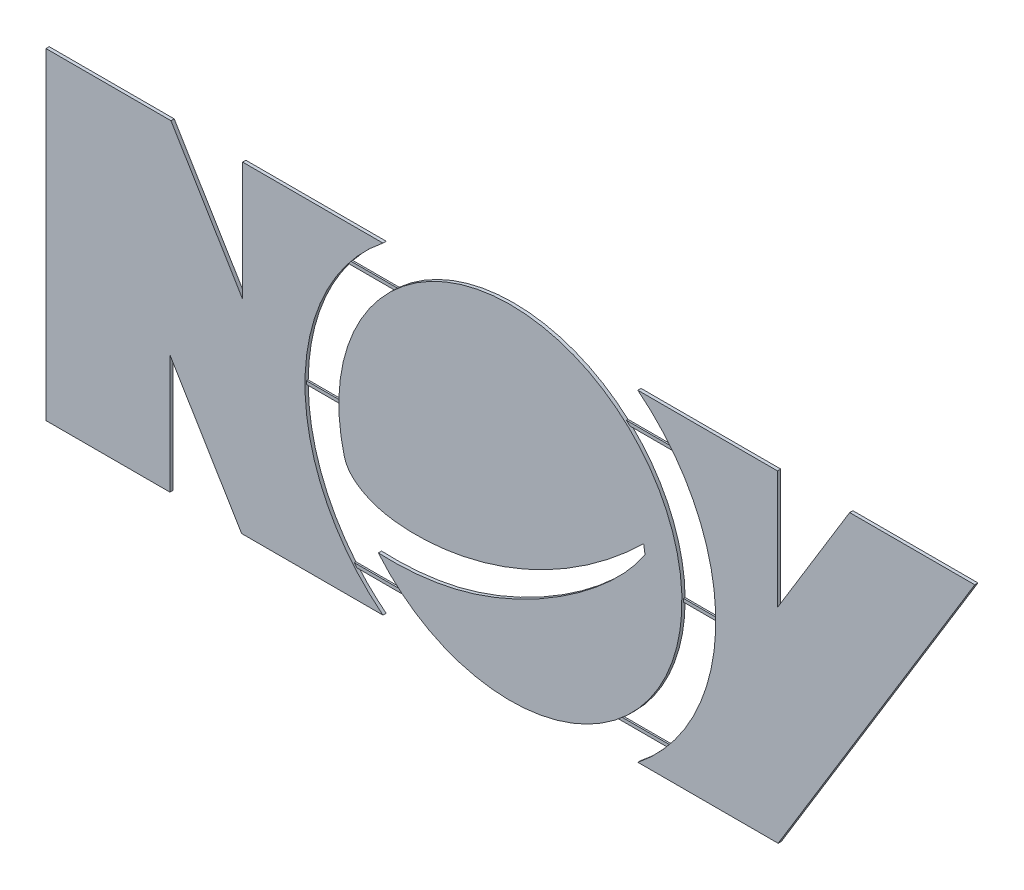
SolidWorks part; units mm, degrees
ref_plane "Front Plane" through (0, 0, 0) normal (0, 0, 1) x (1, 0, 0)
ref_plane "Top Plane" through (0, 0, 0) normal (0, 1, 0) x (1, 0, 0)
ref_plane "Right Plane" through (0, 0, 0) normal (1, 0, 0) x (0, 0, -1)
sketch "Sketch1" plane through (0, 0, 0) normal (0, 0, 1) x (1, 0, 0)
  line L0 (86.6339, 0.0014) -> (86.6339, 64.0014) construction
  line L1 (0, 62.0613) -> (23.3158, 62.0613)
  line L2 (23.3158, 62.0613) -> (36.6891, 39.8873)
  line L3 (36.6891, 39.8873) -> (36.6891, 62.0613)
  line L4 (36.6891, 62.0613) -> (62.8655, 62.0613)
  line L5 (0, 62.0613) -> (0, 1.95)
  line L6 (0, 1.95) -> (23.1112, 1.95)
  line L7 (23.1112, 1.95) -> (23.1112, 24.1454)
  line L8 (23.1112, 24.1454) -> (36.4974, 1.95)
  line L9 (36.4974, 1.95) -> (62.8567, 1.95)
  line L10 (110.412, 1.95) -> (136.5869, 1.95)
  line L11 (136.5869, 1.95) -> (173.2687, 62.0613)
  line L12 (173.2687, 62.0613) -> (149.9284, 62.0613)
  line L13 (149.9284, 62.0613) -> (136.4682, 40.0038)
  line L14 (136.4682, 40.0038) -> (136.4682, 62.0613)
  line L15 (136.4682, 62.0613) -> (110.4031, 62.0613)
  line L16 (0, 64.0043) -> (173.2687, 0) construction
  line L17 (173.2687, 64.0043) -> (0, 64.0043) construction
  line L18 (173.2687, 64.0043) -> (173.2687, 0) construction
  line L19 (173.2687, 0) -> (0, 0) construction
  line L20 (0, 64.0043) -> (0, 0) construction
  line L21 (111.4906, 37.8163) -> (111.7516, 36.1382)
  arc A0 (62.8655, 62.0613) -> (62.8567, 1.95) centre (86.6343, 32.0021) ccw
  arc A1 (110.412, 1.95) -> (110.4031, 62.0613) centre (86.6343, 32.0021) ccw
  arc A2 (61.9998, 11.5748) -> (55.6658, 23.9345) centre (86.6343, 32.0021) ccw
  spline S0 degree 3 poles (61.9998, 11.5748) (65.6518, 11.3847) (84.023, 12.1718) (105.2441, 26.2465) (111.7516, 36.1382) knots 0 0 0 0 0.285158 1 1 1 1
  spline S1 degree 3 poles (55.6207, 24.1096) (56.1961, 21.7048) (60.2552, 18.8924) (68.0001, 17.6879) (77.626, 18.4752) (88.0507, 21.7096) (99.9709, 27.9012) (107.3037, 33.692) (111.4906, 37.8163) knots 0 0 0 0 0.111444 0.211567 0.368518 0.562067 0.722926 1 1 1 1
  dimension "D1" = 64
  dimension "D2" = 1.95
extrude "Boss-Extrude1" add sketch "Sketch1" along normal blind 0.6 contours A0 L4 L3 L2 L1 L5 L6 L7 L8 L9 | A2 S1 L21 S0 | A1 L10 L11 L12 L13 L14 L15
ref_plane "Plane1" through (86.635, 0, 0) normal (-1, 0, 0) x (0, 0, 1)
ref_plane "Plane2" through (0, 32.0056, 0) normal (0, 1, 0) x (1, 0, 0)
sketch "Sketch2" plane through (0, 0, 0) normal (0, 0, 1) x (1, 0, 0)
  line L0 (56.6338, 55.8449) -> (65.2882, 55.8449)
  line L1 (56.1666, 55.2449) -> (64.6364, 55.2449)
  line L2 (110.412, 1.95) -> (136.5869, 1.95) construction
  line L3 (136.5869, 1.95) -> (173.2687, 62.0613) construction
  line L4 (173.2687, 62.0613) -> (149.9284, 62.0613) construction
  line L5 (149.9284, 62.0613) -> (136.4682, 40.0038) construction
  line L6 (136.4682, 40.0038) -> (136.4682, 62.0613) construction
  line L7 (136.4682, 62.0613) -> (110.4031, 62.0613) construction
  line L8 (62.8655, 62.0613) -> (36.6891, 62.0613) construction
  line L9 (36.6891, 62.0613) -> (36.6891, 39.8873) construction
  line L10 (36.6891, 39.8873) -> (23.3158, 62.0613) construction
  line L11 (23.3158, 62.0613) -> (0, 62.0613) construction
  line L12 (0, 62.0613) -> (0, 1.95) construction
  line L13 (0, 1.95) -> (23.1112, 1.95) construction
  line L14 (23.1112, 1.95) -> (23.1112, 24.1454) construction
  line L15 (23.1112, 24.1454) -> (36.4974, 1.95) construction
  line L16 (36.4974, 1.95) -> (62.8567, 1.95) construction
  line L17 (111.4906, 37.8163) -> (111.7516, 36.1382) construction
  line L18 (110.412, 1.95) -> (136.5869, 1.95)
  line L19 (136.5869, 1.95) -> (173.2687, 62.0613)
  line L20 (173.2687, 62.0613) -> (149.9284, 62.0613)
  line L21 (149.9284, 62.0613) -> (136.4682, 40.0038)
  line L22 (136.4682, 40.0038) -> (136.4682, 62.0613)
  line L23 (136.4682, 62.0613) -> (110.4031, 62.0613)
  line L24 (62.8655, 62.0613) -> (36.6891, 62.0613)
  line L25 (36.6891, 62.0613) -> (36.6891, 39.8873)
  line L26 (36.6891, 39.8873) -> (23.3158, 62.0613)
  line L27 (23.3158, 62.0613) -> (0, 62.0613)
  line L28 (0, 62.0613) -> (0, 1.95)
  line L29 (0, 1.95) -> (23.1112, 1.95)
  line L30 (23.1112, 1.95) -> (23.1112, 24.1454)
  line L31 (23.1112, 24.1454) -> (36.4974, 1.95)
  line L32 (36.4974, 1.95) -> (62.8567, 1.95)
  line L33 (111.4906, 37.8163) -> (111.7516, 36.1382)
  line L34 (48.3151, 32.3863) -> (54.6345, 32.3863)
  line L35 (48.3138, 31.7863) -> (54.6329, 31.7863)
  line L36 (57.2015, 7.4621) -> (66.0936, 7.4621)
  line L37 (57.7123, 6.8621) -> (66.8325, 6.8621)
  line L38 (116.0672, 7.4621) -> (107.1751, 7.4621)
  line L39 (115.5564, 6.8621) -> (106.4362, 6.8621)
  line L40 (124.9535, 32.3863) -> (118.6342, 32.3863)
  line L41 (124.9549, 31.7863) -> (118.6357, 31.7863)
  line L42 (117.1021, 55.2449) -> (108.6323, 55.2449)
  line L43 (116.6348, 55.8449) -> (107.9805, 55.8449)
  arc A0 (62.8655, 62.0613) -> (62.8567, 1.95) centre (86.6343, 32.0021) ccw construction
  arc A1 (61.9998, 11.5748) -> (55.6658, 23.9345) centre (86.6343, 32.0021) ccw construction
  arc A2 (110.412, 1.95) -> (110.4031, 62.0613) centre (86.6343, 32.0021) ccw construction
  arc A3 (62.8655, 62.0613) -> (62.8567, 1.95) centre (86.6343, 32.0021) ccw construction
  arc A4 (110.412, 1.95) -> (110.4031, 62.0613) centre (86.6343, 32.0021) ccw
  arc A5 (62.8655, 62.0613) -> (62.8567, 1.95) centre (86.6343, 32.0021) ccw
  arc A6 (61.9998, 11.5748) -> (55.6658, 23.9345) centre (86.6343, 32.0021) ccw
  spline S0 degree 3 poles (1936.382, 700.1061) (24.2852, 109.4543) (36.9497, 22.5168) (68.0001, 17.6879) (77.626, 18.4752) (88.0507, 21.7096) (229.6471, 95.259) (107.5698, 583.7012) (-1609.4835, -920.0756) knots -1.10892 -1.10892 -1.10892 -1.10892 0.111444 0.211567 0.368518 0.562067 0.722926 7.869722 7.869722 7.869722 7.869722 only from (55.6658, 23.9345) to (111.4906, 37.8163) construction
  spline S1 degree 3 poles (-1737.8727, -714.4512) (294.8147, 299.4838) (57.091, -167.8769) (-18.0464, 122.8026) (1968.3755, -590.4602) knots -3.597505 -3.597505 -3.597505 -3.597505 0.714842 3.955537 3.955537 3.955537 3.955537 only from (111.7516, 36.1382) to (61.9998, 11.5748) construction
  spline S2 degree 3 poles (55.6658, 23.9345) (56.301, 21.6325) (60.3126, 18.8835) (68.0001, 17.6879) (77.626, 18.4752) (88.0507, 21.7096) (99.9709, 27.9012) (107.3037, 33.692) (111.4906, 37.8163) knots 0.002731 0.002731 0.002731 0.002731 0.111444 0.211567 0.368518 0.562067 0.722926 1 1 1 1
  spline S3 degree 3 poles (111.7516, 36.1382) (105.2441, 26.2465) (84.023, 12.1718) (65.6518, 11.3847) (61.9998, 11.5748) knots 0 0 0 0 0.714842 1 1 1 1
  dimension "D1" = 0.6
  dimension "D2" = 0.6
  dimension "D3" = 0.6
  dimension "D4" = 0.6
  dimension "D5" = 0.6
  dimension "D6" = 0.6
extrude "Boss-Extrude2" add sketch "Sketch2" along normal blind 0.3 contours A6 L0 A5 L1 | A6 L36 A5 L37 | A6 L34 A5 L35 | A6 L39 A4 L38 | A6 L41 A4 L40 | A6 L42 A4 L43
